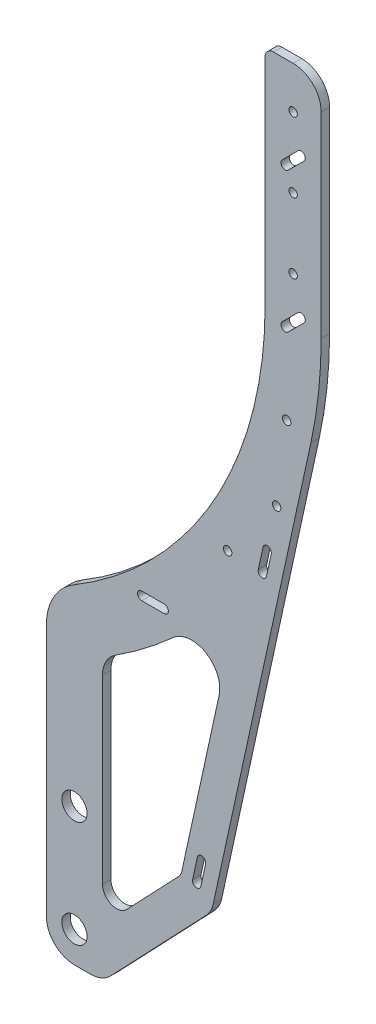
SolidWorks part; units mm, degrees
material "Thornel Mat VMA"
ref_plane "前视基准面" through (0, 0, 0) normal (0, 0, 1) x (1, 0, 0)
ref_plane "上视基准面" through (0, 0, 0) normal (0, 1, 0) x (1, 0, 0)
ref_plane "右视基准面" through (0, 0, 0) normal (1, 0, 0) x (0, 0, -1)
sketch "草图1" plane through (0, 0, 0) normal (0, 0, 1) x (1, 0, 0)
  line L9 (-10, 49) -> (10, 49)
  line L10 (-10, 49) -> (-10, -11)
  line L11 (-10, -11) -> (10, -11)
  line L12 (10, 49) -> (10, -11)
  line L13 (-10, 49) -> (10, -11) construction
  line L14 (-10, -11) -> (10, 49) construction
  circle A2 centre (0, 0) radius 4.5
  circle A3 centre (0, 38) radius 4.5
  point P5 (0, 19)
  dimension "D1" = 9
  dimension "D2" = 9
  dimension "D3" = 38
  dimension "D4" = 60
  dimension "D5" = 20
  dimension "D6" = 19
extrude "凸台-拉伸1" add sketch "草图1" along normal blind 3
sketch "草图3" plane through (0, 0, 3) normal (0, 0, 1) x (1, 0, 0)
  line L0 (-10, 49) -> (-10, 100.9771)
  line L1 (10, 49) -> (10, 89.11)
  line L2 (88, 226.5) -> (88, 306.5)
  line L3 (-72, 504.444) -> (-72, -52.4105) construction
  line L4 (88, 306.5) -> (68, 306.5)
  line L5 (68, 306.5) -> (68, 226.5)
  circle A1 centre (-72, 226.5) radius 140
  circle A2 centre (-72, 226.5) radius 160
  dimension "D1" = 280
  dimension "D4" = 320
  dimension "D2" = 226.5
  dimension "D3" = 72
  dimension "D5" = 80
  dimension "D6" = 20
extrude "凸台-拉伸2" add sketch "草图3" against normal blind 3
sketch "草图4" plane through (0, 0, 0) normal (0, 0, -1) x (-1, 0, 0)
  line L0 (-10, -11) -> (-40, -11)
  line L1 (-40, -11) -> (-84.3312, 192.433)
  line L2 (-10, -11) -> (-10, -1)
  line L3 (-10, -11) -> (-10, 89.11) construction
  line L4 (-10, -1) -> (-30, -1)
  line L5 (-30, -1) -> (-59.8119, 135.8047)
  circle A0 centre (72, 226.5) radius 160
  arc A1 (-88, 226.5) -> (-10, 89.11) centre (72, 226.5) ccw construction
  line M8 (-10, 89.11) -> (-10, -11)
  arc M15 (-88, 226.5) -> (-10, 89.11) centre (72, 226.5) ccw
  dimension "D1" = 30
  dimension "D2" = 10
  dimension "D3" = 20
extrude "凸台-拉伸3" add sketch "草图4" against normal blind 3 contours L4 L5 L1 L0 M15 M8
fillet "圆角2" radius 10 3 edges at (88, 306.5, 1.5) (-10, -11, 1.5) (40, -11, 1.5)
fillet "圆角3" radius 20 1 edges at (-10, 100.9771, 1.5)
fillet "圆角4" radius 3 1 edges at (68, 306.5, 1.5)
sketch "草图5" plane through (0, 0, 3) normal (0, 0, 1) x (1, 0, 0)
  line L0 (41.7152, -3.1292) -> (84.3312, 192.433) construction
  line L1 (46.7784, 43.5889) -> (43.8472, 44.2277)
  line L2 (46.7784, 43.5889) -> (45.0751, 35.7723)
  line L3 (45.0751, 35.7723) -> (42.1439, 36.4111)
  line L4 (43.8472, 44.2277) -> (42.1439, 36.4111)
  line L5 (46.7784, 43.5889) -> (42.1439, 36.4111) construction
  line L6 (45.0751, 35.7723) -> (43.8472, 44.2277) construction
  line L7 (70.1995, 151.0666) -> (68.4961, 143.25)
  line L8 (70.1995, 151.0666) -> (67.2683, 151.7054)
  line L9 (67.2683, 151.7054) -> (65.5649, 143.8888)
  line L10 (68.4961, 143.25) -> (65.5649, 143.8888)
  line L11 (78, 306.5) -> (78, 178.7882) construction
  line L12 (24, 116.5) -> (32, 116.5)
  line L13 (24, 116.5) -> (24, 113.5)
  line L14 (24, 113.5) -> (32, 113.5)
  line L15 (32, 116.5) -> (32, 113.5)
  line L16 (24, 116.5) -> (32, 113.5) construction
  line L17 (24, 113.5) -> (32, 116.5) construction
  line L18 (79.7678, 280.3891) -> (74.1109, 274.7322)
  line L19 (79.7678, 230.3891) -> (81.8891, 228.2678)
  line L20 (79.7678, 230.3891) -> (74.1109, 224.7322)
  line L21 (74.1109, 224.7322) -> (76.2322, 222.6109)
  line L22 (81.8891, 228.2678) -> (76.2322, 222.6109)
  line L23 (79.7678, 230.3891) -> (76.2322, 222.6109) construction
  line L24 (74.1109, 224.7322) -> (81.8891, 228.2678) construction
  line L25 (79.7678, 280.3891) -> (81.8891, 278.2678)
  line L26 (81.8891, 278.2678) -> (76.2322, 272.6109)
  line L27 (74.1109, 274.7322) -> (76.2322, 272.6109)
  point P0 (44.4611, 40)
  point P7 (28, 115)
  point P19 (78, 226.5)
  dimension "D1" = 8
  dimension "D2" = 3
  dimension "D3" = 5
  dimension "D4" = 40
  dimension "D6" = 110
  dimension "D7" = 3
  dimension "D8" = 8
  dimension "D9" = 28
  dimension "D10" = 115
  dimension "D11" = 8
  dimension "D12" = 3
  dimension "D13" = 80
  dimension "D5" = 2
  dimension "D14" = 2
extrude "切除-拉伸1" cut sketch "草图5" against normal through all
sketch "草图7" plane through (0, 0, 0) normal (0, 0, -1) x (-1, 0, 0)
  line L0 (72, 500.698) -> (72, -30.0553) construction
  line L1 (72, 226.5) -> (-72.1252, 166.8014) construction
  line L2 (72, 226.5) -> (-75.7003, 195.1053) construction
  circle A0 centre (72, 226.5) radius 156 construction
  circle A1 centre (-72.1252, 166.8014) radius 1.5
  circle A2 centre (72, 226.5) radius 151 construction
  circle A3 centre (-75.7003, 195.1053) radius 1.5
  circle A4 centre (-54.6393, 144.2595) radius 1.5
  dimension "D1" = 312
  dimension "D2" = 3
  dimension "D4" = 302
  dimension "D5" = 3
  dimension "D3" = 67.5
  dimension "D6" = 10.5
extrude "切除-拉伸2" cut sketch "草图7" against normal through all
sketch "草图8" plane through (0, 0, 3) normal (0, 0, 1) x (1, 0, 0)
  line L0 (37.2688, 32.3561) -> (48.8958, 29.8224)
  line L1 (30, -1) -> (59.8119, 135.8047) construction
  line L2 (41.7152, -3.1292) -> (84.3312, 192.433) construction
  line L3 (48.8958, 29.8224) -> (39.1711, -58.6462)
  line L4 (39.1711, -58.6462) -> (10, -11)
  line L5 (0, -11) -> (31.9445, -11) construction
  line L6 (10, -11) -> (10, -1)
  line L7 (10, -1) -> (37.2688, 32.3561)
  line L8 (42.1439, 36.4111) -> (45.0751, 35.7723) construction
  point P14 (43.6095, 36.0917)
  line M29 (30, -1) -> (10, -1)
  line M32 (59.8119, 135.8047) -> (30, -1)
  line M41 (0, -11) -> (31.9445, -11)
  arc M42 (31.9445, -11) -> (41.7152, -3.1292) centre (31.9445, -1) ccw
  dimension "D1" = 5
extrude "切除-拉伸4" cut sketch "草图8" against normal blind 10 contours L4 L3 M42 M41 | L7 M29 M32 | L6 L3 L0 M41 M42 M32 M29
sketch "草图9" plane through (0, 0, 3) normal (0, 0, 1) x (1, 0, 0)
  line L0 (48.8958, 29.8224) -> (10, -11)
  line L2 (10, -11) -> (10, 89.11) construction
  line L3 (37.2688, 32.3561) -> (48.8958, 29.8224)
  line L4 (10, -0.0391) -> (10, -11)
  line L5 (10, 6.3959) -> (38.0202, 35.804)
  line L6 (37.2688, 32.3561) -> (59.8119, 135.8047) construction
  line L7 (10, 6.3959) -> (10, -0.0391)
  line L8 (38.0202, 35.804) -> (37.2688, 32.3561)
  dimension "D1" = 12
extrude "凸台-拉伸4" add sketch "草图9" against normal blind 3
fillet "圆角5" radius 10 2 edges at (10, -11, 1.5) (48.8958, 29.8224, 1.5)
fillet "圆角6" radius 10 2 edges at (59.8119, 135.8047, 1.5) (10, 89.11, 1.5)
fillet "圆角7" radius 5 2 edges at (38.0202, 35.804, 1.5) (10, 6.3959, 1.5)
sketch "草图11" plane through (0, 0, 3) normal (0, 0, 1) x (1, 0, 0)
  line L0 (24, 116.5) -> (24, 113.5) construction
  line L1 (32, 113.5) -> (32, 116.5) construction
  line L2 (42.1439, 36.4111) -> (45.0751, 35.7723) construction
  line L3 (46.7784, 43.5889) -> (43.8472, 44.2277) construction
  line L4 (65.5649, 143.8888) -> (68.4961, 143.25) construction
  line L5 (70.1995, 151.0666) -> (67.2683, 151.7054) construction
  line L6 (81.8891, 228.2678) -> (79.7678, 230.3891) construction
  line L7 (74.1109, 224.7322) -> (76.2322, 222.6109) construction
  line L8 (81.8891, 278.2678) -> (79.7678, 280.3891) construction
  line L9 (74.1109, 274.7322) -> (76.2322, 272.6109) construction
  circle A0 centre (24, 115) radius 1.5
  circle A1 centre (32, 115) radius 1.5
  circle A2 centre (43.6095, 36.0917) radius 1.5
  circle A3 centre (45.3128, 43.9083) radius 1.5
  circle A4 centre (67.0305, 143.5694) radius 1.5
  circle A5 centre (68.7339, 151.386) radius 1.5
  circle A6 centre (80.8284, 229.3284) radius 1.5
  circle A7 centre (75.1716, 223.6716) radius 1.5
  circle A8 centre (80.8284, 279.3284) radius 1.5
  circle A9 centre (75.1716, 273.6716) radius 1.5
extrude "切除-拉伸6" cut sketch "草图11" against normal through all
sketch "草图12" plane through (0, 0, 0) normal (0, 0, -1) x (-1, 0, 0)
  line L0 (-68, 226.5) -> (-88, 226.5) construction
  line L1 (-78, 226.5) -> (-78, 306.5) construction
  line L2 (-78, 306.5) -> (-71, 306.5) construction
  circle A0 centre (-78, 291.5) radius 1.5
  circle A1 centre (-78, 266.5) radius 1.5
  circle A2 centre (-78, 241.5) radius 1.5
  dimension "D1" = 15
  dimension "D2" = 3
  dimension "D3" = 3
extrude "切除-拉伸7" cut sketch "草图12" against normal through all
